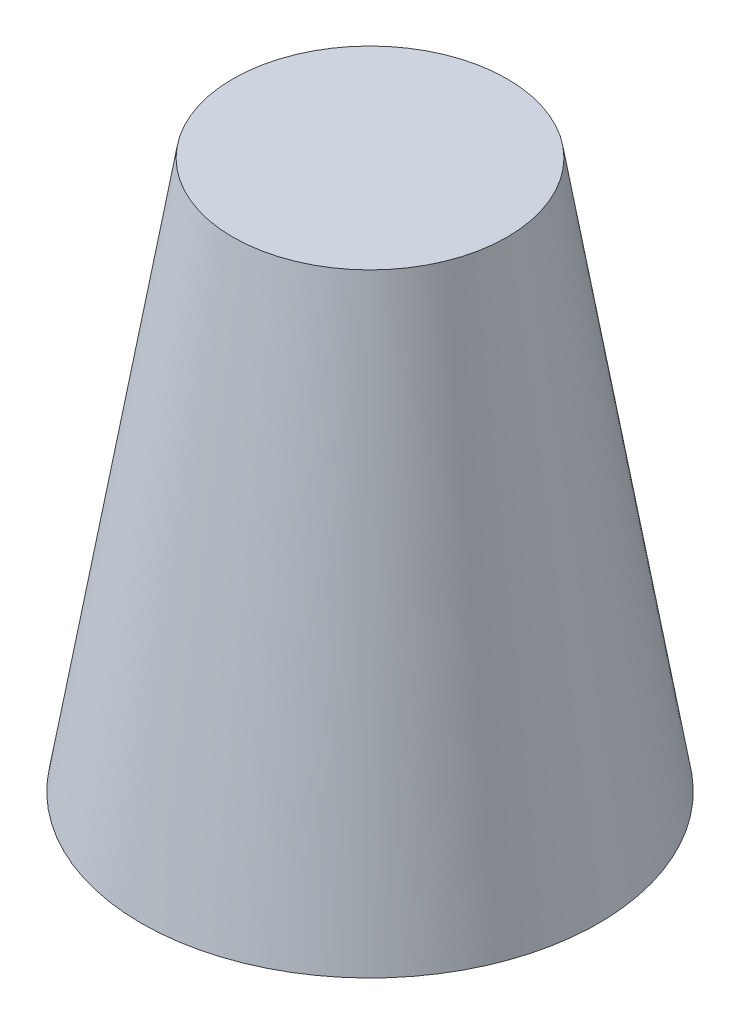
SolidWorks part; units mm, degrees
ref_plane "前视基准面" through (0, 0, 0) normal (0, 0, 1) x (1, 0, 0)
ref_plane "上视基准面" through (0, 0, 0) normal (0, 1, 0) x (1, 0, 0)
ref_plane "右视基准面" through (0, 0, 0) normal (1, 0, 0) x (0, 0, -1)
other "Configuration Table"
sketch "草图1" plane through (0, 0, 0) normal (1, 0, 0) x (0, 0, -1)
  line L0 (0, 0) -> (0, 25.6667) construction
  line L1 (0, 0) -> (25, 0)
  line L2 (25, 0) -> (15, 60)
  line L3 (15, 60) -> (0, 60)
  line L4 (0, 60) -> (0, 0)
  dimension "D1" = 25
  dimension "D2" = 15
  dimension "D3" = 60
revolve "旋转1" add sketch "草图1" angle 360 about L0
